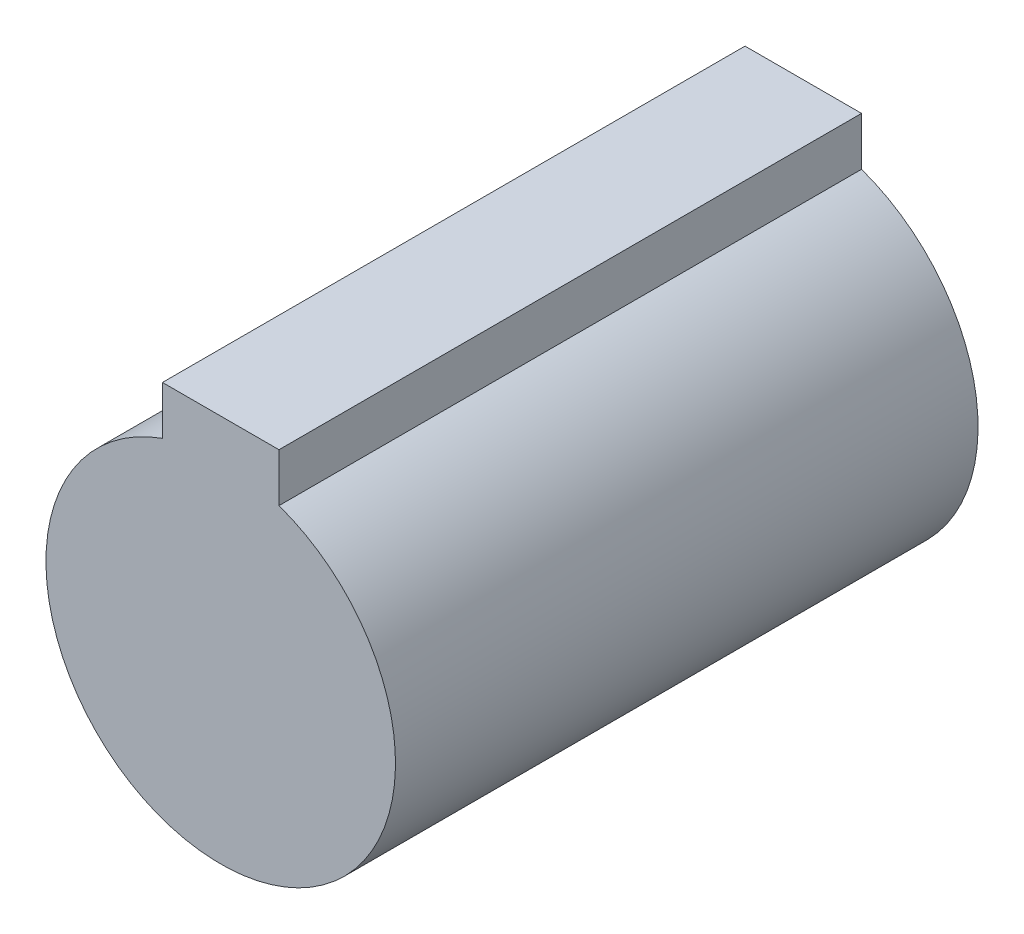
SolidWorks part; units mm, degrees
material "Galvanized Steel"
ref_plane "Front Plane" through (0, 0, 0) normal (0, 0, 1) x (1, 0, 0)
ref_plane "Top Plane" through (0, 0, 0) normal (0, 1, 0) x (1, 0, 0)
ref_plane "Right Plane" through (0, 0, 0) normal (1, 0, 0) x (0, 0, -1)
sketch "Sketch1" plane through (0, 0, 0) normal (0, 0, 1) x (1, 0, 0)
  line L0 (-5, 14.1421) -> (-5, 18.3)
  line L1 (5, 18.3) -> (5, 14.1421)
  line L2 (-5, 18.3) -> (5, 18.3)
  arc A0 (-5, 14.1421) -> (5, 14.1421) centre (0, 0) ccw
  point P5 (0, 0)
  dimension "D1" = 15
  dimension "D2" = 10
  dimension "D3" = 18.3
  dimension "D4" = 5
extrude "Boss-Extrude1" add sketch "Sketch1" along normal blind 50
